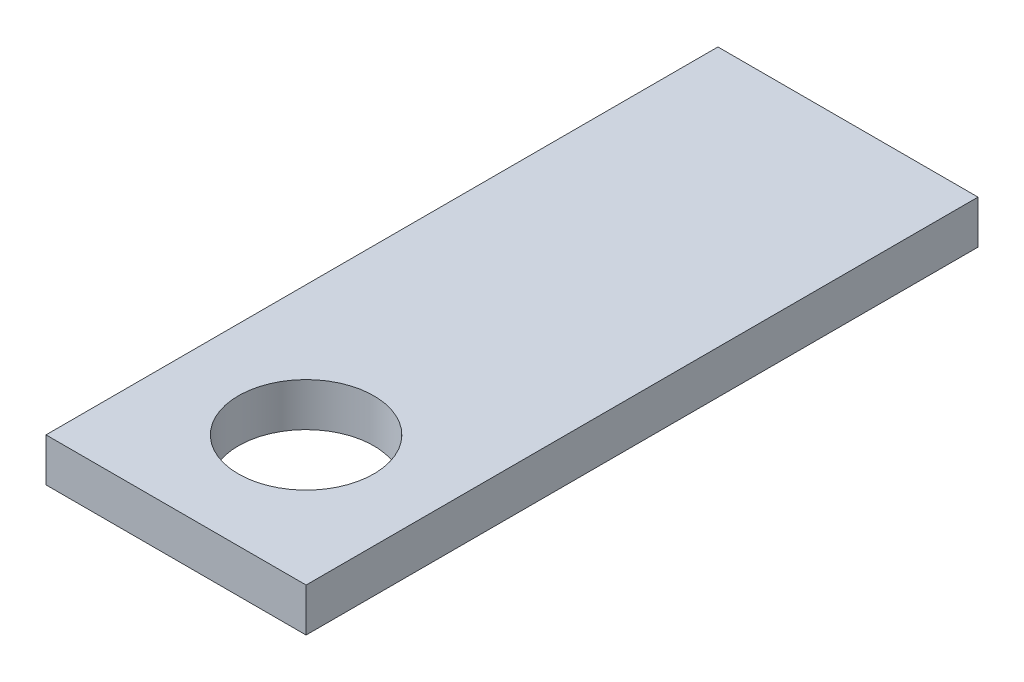
SolidWorks part; units mm, degrees
material "Plain Carbon Steel"
ref_plane "Front Plane" through (0, 0, 0) normal (0, 0, 1) x (1, 0, 0)
ref_plane "Top Plane" through (0, 0, 0) normal (0, 1, 0) x (1, 0, 0)
ref_plane "Right Plane" through (0, 0, 0) normal (1, 0, 0) x (0, 0, -1)
sketch "Sketch1" plane through (0, 0, 0) normal (0, 0, 1) x (1, 0, 0)
  line L1 (-19.05, -3.175) -> (19.05, -3.175)
  line L2 (-19.05, -3.175) -> (-19.05, 3.175)
  line L3 (-19.05, 3.175) -> (19.05, 3.175)
  line L4 (19.05, -3.175) -> (19.05, 3.175)
  line L5 (-19.05, -3.175) -> (19.05, 3.175) construction
  line L6 (-19.05, 3.175) -> (19.05, -3.175) construction
  point P0 (0, 0)
  dimension "D1" = 38.1
  dimension "D2" = 6.35
extrude "Extrude1" add sketch "Sketch1" along normal blind 98.425
sketch "Sketch2" plane through (0, 3.175, 0) normal (0, 1, 0) x (1, 0, 0)
  line L0 (0, -98.425) -> (0, -79.375) construction
  line L1 (19.05, -98.425) -> (-19.05, -98.425) construction
  dimension "D1" = 19.05
hole_wizard "3/4 Clearance Hole1" positions "3DSketch1" profile "Sketch3" hole size "3/4" standard "Ansi Inch"
sketch3d "3DSketch1"
  point P0 (0, 3.175, 79.375)
sketch "Sketch3" plane through (0, 3.175, 79.375) normal (1, 0, 0) x (0, 0, 1)
  line L0 (0, 0) -> (0, 21.9633)
  line L1 (0, 21.9633) -> (9.9212, 16.002)
  line L2 (9.9212, 16.002) -> (9.9212, 0)
  line L5 (9.9212, 0) -> (0, 0)
  line L10 (0, 21.9633) -> (-9.9212, 16.002) construction
  line L11 (0, -6.35) -> (0, 107.95) construction
  dimension "Hole Dia." = 19.8425
  dimension "Hole Depth" = 16.002
  dimension "Drill Angle" = 118
